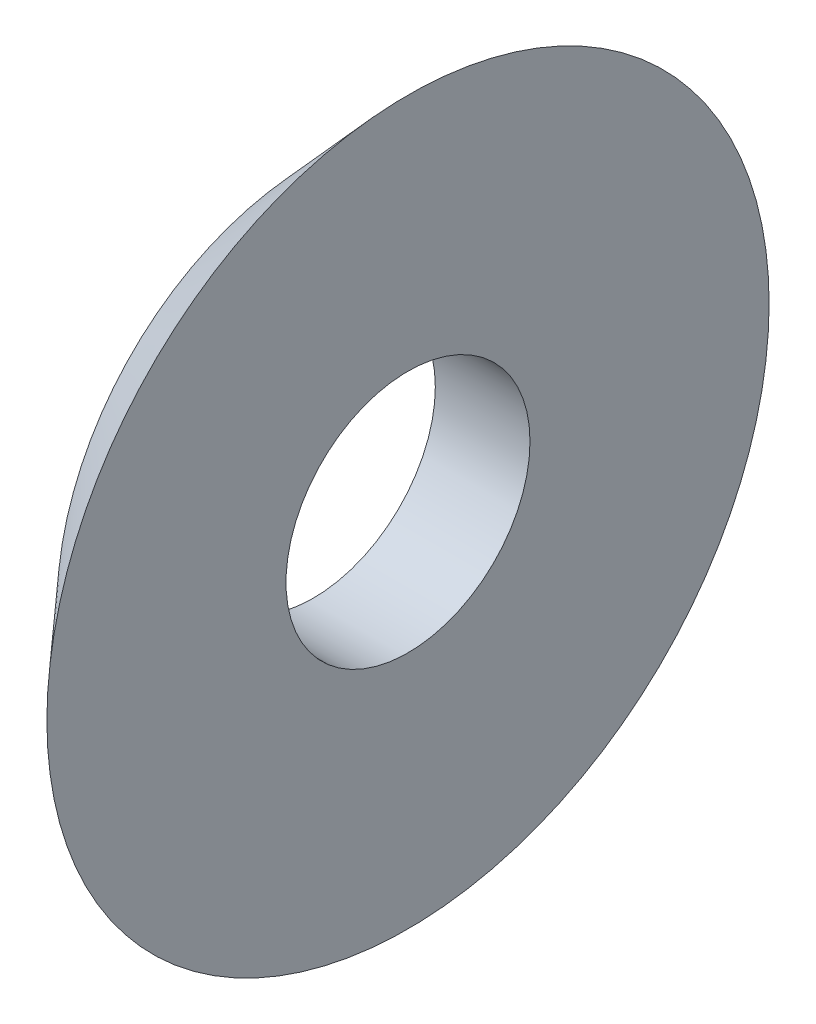
SolidWorks part; units mm, degrees
material "6061 Alloy"
ref_plane "Front" through (0, 0, 0) normal (0, 0, 1) x (1, 0, 0)
ref_plane "Top" through (0, 0, 0) normal (0, 1, 0) x (1, 0, 0)
ref_plane "Right" through (0, 0, 0) normal (1, 0, 0) x (0, 0, -1)
sketch "Sketch2" plane through (0, 0, 0) normal (0, 0, 1) x (1, 0, 0)
  line L0 (0, 0) -> (-4.8888, 0) construction
  line L1 (-1.94, 2.5) -> (-1.94, 5.25)
  line L2 (-1.94, 5.25) -> (0, 7.4)
  line L3 (0, 7.4) -> (0, 2.5)
  line L4 (0, 0) -> (-1.94, 0) construction
  line L5 (-1.94, 2.5) -> (0, 2.5)
  dimension "D1" = 1.94
  dimension "D2" = 14.8
  dimension "D3" = 10.5
  dimension "D4" = 1.94
  dimension "D5" = 5
revolve "Revolve1" add sketch "Sketch2" angle 360 about L0
